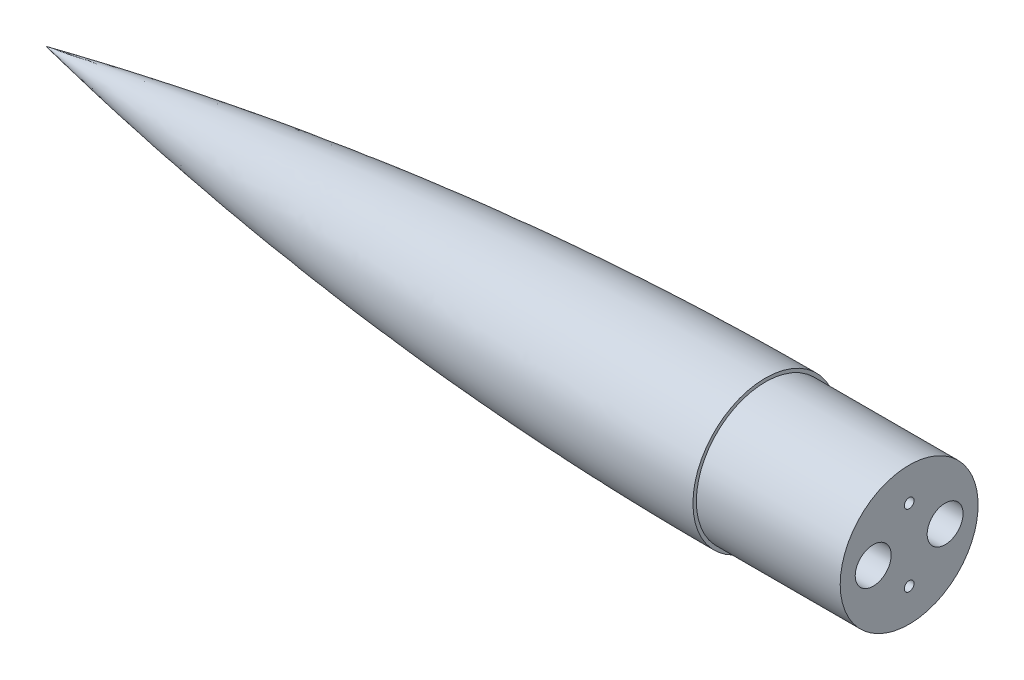
SolidWorks part; units mm, degrees
ref_plane "Front Plane" through (0, 0, 0) normal (0, 0, 1) x (1, 0, 0)
ref_plane "Top Plane" through (0, 0, 0) normal (0, 1, 0) x (1, 0, 0)
ref_plane "Right Plane" through (0, 0, 0) normal (1, 0, 0) x (0, 0, -1)
sketch "Sketch2" plane through (0, 0, 0) normal (0, 0, 1) x (1, 0, 0)
  line L0 (0, 0) -> (508, 0)
  line L1 (508, 0) -> (508, 51.1048)
  spline S0 degree 4 poles (-49.784, -10.6374) (-48.7345, -10.4022) (-46.6465, -9.9353) (-43.4882, -9.2333) (-39.3155, -8.3125) (-35.111, -7.3928) (-30.9967, -6.4991) (-26.7845, -5.5929) (-22.778, -4.7359) (-18.4595, -3.8226) (-14.6536, -3.0205) (-9.9942, -2.0521) (-6.7505, -1.3786) (-1.3953, -0.2833) (0.8538, 0.1742) (5.3909, 1.0913) (8.4055, 1.6943) (12.0238, 2.4152) (15.3299, 3.0678) (18.8115, 3.7511) (22.1942, 4.4096) (25.6534, 5.0785) (29.1014, 5.74) (33.4595, 6.5702) (38.7038, 7.5588) (44.8308, 8.6992) (51.8331, 9.9822) (58.8409, 11.2461) (65.8511, 12.4902) (72.8653, 13.7148) (79.8826, 14.9198) (86.9035, 16.1052) (93.9274, 17.271) (100.9547, 18.4172) (109.7428, 19.8254) (120.2947, 21.476) (146.6934, 25.4796) (189.0132, 31.335) (234.9835, 36.7388) (281.0601, 41.1143) (312.999, 43.6682) (330.7529, 44.9548) (344.9614, 45.9048) (359.1751, 46.7755) (371.6161, 47.4678) (382.2825, 48.0117) (391.1727, 48.4318) (398.286, 48.748) (405.3996, 49.0444) (412.5149, 49.3209) (421.4082, 49.6417) (430.3056, 49.9294) (439.1993, 50.1839) (448.1007, 50.4054) (455.2122, 50.5627) (462.3439, 50.7001) (468.5513, 50.803) (473.9242, 50.8787) (479.1708, 50.944) (484.5437, 50.9992) (490.4442, 51.0493) (496.8818, 51.0826) (501.5851, 51.0992) (507.0844, 51.1054) (509.4557, 51.1051) (514.8153, 51.0984) (518.2713, 51.0846) (523.9402, 51.0585) (529.9661, 51.0134) (536.5026, 50.9507) (542.7269, 50.8703) (548.1166, 50.7912) (551.8184, 50.7291) (555.0628, 50.6714) (557.1894, 50.6305) (558.2634, 50.6095) (558.8013, 50.5988) knots 0 0 0 0 0 0.007004 0.014007 0.021011 0.028014 0.034891 0.041768 0.048645 0.055522 0.062399 0.069276 0.076153 0.08303 0.088712 0.094393 0.100074 0.105755 0.111436 0.117117 0.122799 0.12848 0.134286 0.140092 0.151705 0.163318 0.174931 0.186543 0.198156 0.209769 0.221381 0.232994 0.244607 0.256219 0.267832 0.291057 0.314283 0.43041 0.546537 0.592987 0.616213 0.639438 0.662663 0.685889 0.709114 0.720727 0.73234 0.743952 0.755565 0.767178 0.77879 0.802016 0.813628 0.825241 0.836854 0.848467 0.860079 0.865886 0.871692 0.883054 0.894417 0.905779 0.91146 0.917141 0.924004 0.930867 0.93773 0.944592 0.958318 0.972044 0.979033 0.986022 0.993011 0.996505 1 1 1 1 1 construction
  spline S1 degree 4 poles (0, 0) (0.7118, 0.1447) (2.1582, 0.4379) (5.3909, 1.0913) (8.4055, 1.6943) (12.0238, 2.4152) (15.3299, 3.0678) (18.8115, 3.7511) (22.1942, 4.4096) (25.6534, 5.0785) (29.1014, 5.74) (33.4595, 6.5702) (38.7038, 7.5588) (44.8308, 8.6992) (51.8331, 9.9822) (58.8409, 11.2461) (65.8511, 12.4902) (72.8653, 13.7148) (79.8826, 14.9198) (86.9035, 16.1052) (93.9274, 17.271) (100.9547, 18.4172) (109.7428, 19.8254) (120.2947, 21.476) (146.6934, 25.4796) (189.0132, 31.335) (234.9835, 36.7388) (281.0601, 41.1143) (312.999, 43.6682) (330.7529, 44.9548) (344.9614, 45.9048) (359.1751, 46.7755) (371.6161, 47.4678) (382.2825, 48.0117) (391.1727, 48.4318) (398.286, 48.748) (405.3996, 49.0444) (412.5149, 49.3209) (421.4082, 49.6417) (430.3056, 49.9294) (439.1993, 50.1839) (448.1007, 50.4054) (455.2122, 50.5627) (462.3439, 50.7001) (468.5513, 50.803) (473.9242, 50.8787) (479.1708, 50.944) (484.5437, 50.9992) (490.4442, 51.0493) (496.8818, 51.0826) (501.5851, 51.0992) (505.8089, 51.104) (507.2736, 51.1048) (508, 51.1048) knots 0.08303 0.08303 0.08303 0.08303 0.08303 0.088712 0.094393 0.100074 0.105755 0.111436 0.117117 0.122799 0.12848 0.134286 0.140092 0.151705 0.163318 0.174931 0.186543 0.198156 0.209769 0.221381 0.232994 0.244607 0.256219 0.267832 0.291057 0.314283 0.43041 0.546537 0.592987 0.616213 0.639438 0.662663 0.685889 0.709114 0.720727 0.73234 0.743952 0.755565 0.767178 0.77879 0.802016 0.813628 0.825241 0.836854 0.848467 0.860079 0.865886 0.871692 0.883054 0.894417 0.905779 0.91146 0.917141 0.917141 0.917141 0.917141 0.917141
revolve "Revolve1" add sketch "Sketch2" angle 360 about L0
sketch "Sketch3" plane through (508, 0, 0) normal (1, 0, 0) x (0, 0, -1)
  circle A0 centre (0, 0) radius 48.7045
  dimension "D1" = 97.409
extrude "Boss-Extrude1" add sketch "Sketch3" along normal blind 76.2
sketch "Sketch4" plane through (584.2, 0, 0) normal (1, 0, 0) x (0, 0, -1)
  line L0 (0, 48.7045) -> (0, -48.7045) construction
  circle A0 centre (0, 0) radius 48.7045 construction
  circle A1 centre (0, 0) radius 48.7045 construction
  circle A2 centre (-25.4, 0) radius 12.7
  dimension "D1" = 25.4
  dimension "D2" = 25.4
revolve "Cut-Revolve1" cut sketch "Sketch4" angle 360 about L0
sketch "Sketch5" plane through (584.2, 0, 0) normal (1, 0, 0) x (0, 0, -1)
  circle A0 centre (0, 0) radius 48.7045
  circle A1 centre (-25.4, 0) radius 12.7
  circle A2 centre (25.4, 0) radius 12.7
extrude "Boss-Extrude2" add sketch "Sketch5" along normal blind 25.4
sketch "Sketch6" plane through (609.6, 0, 0) normal (1, 0, 0) x (0, 0, -1)
  line L0 (0, 48.7045) -> (0, -48.7045) construction
  circle A0 centre (0, 0) radius 48.7045 construction
  circle A1 centre (0, 0) radius 48.7045 construction
  circle A2 centre (0, 25.4) radius 3.429
  circle A3 centre (0, -25.4) radius 3.429
  dimension "D1" = 6.858
  dimension "D2" = 6.858
  dimension "D3" = 25.4
  dimension "D4" = 25.4
extrude "Cut-Extrude1" cut sketch "Sketch6" against normal blind 355.6
